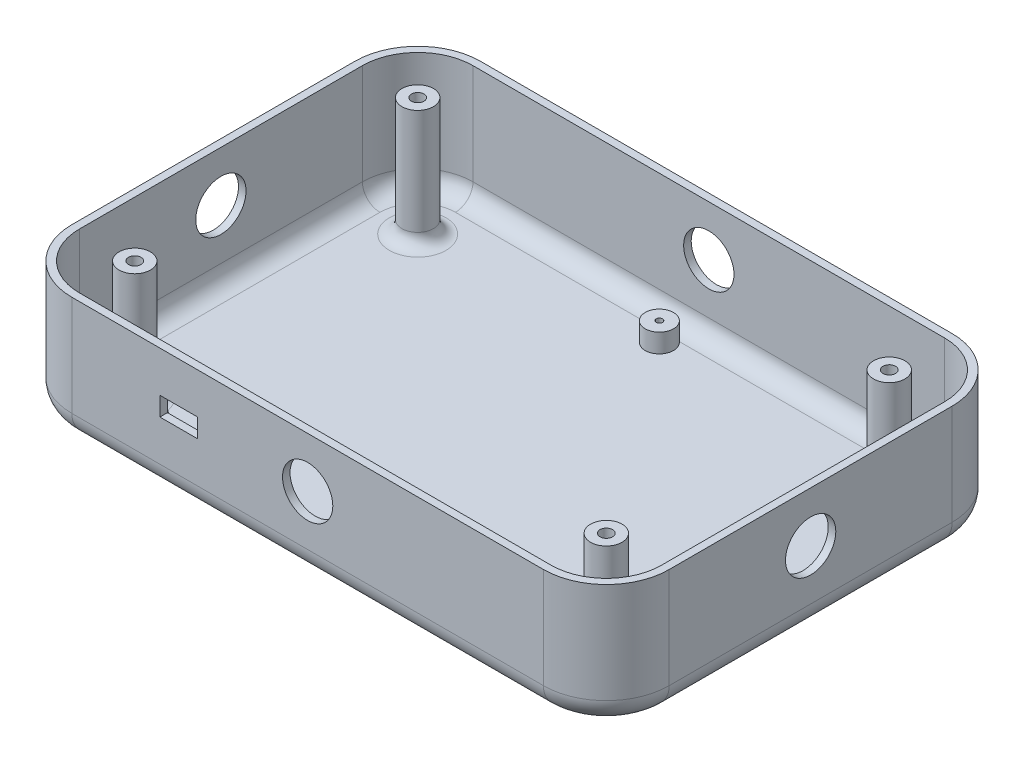
SolidWorks part; units mm, degrees
ref_plane "Front Plane" through (0, 0, 0) normal (0, 0, 1) x (1, 0, 0)
ref_plane "Top Plane" through (0, 0, 0) normal (0, 1, 0) x (1, 0, 0)
ref_plane "Right Plane" through (0, 0, 0) normal (1, 0, 0) x (0, 0, -1)
sketch "Sketch1" plane through (0, 0, 0) normal (0, 1, 0) x (1, 0, 0)
  line L1 (0, 0) -> (95, 0)
  line L2 (0, 0) -> (0, 65)
  line L3 (0, 65) -> (95, 65)
  line L4 (95, 0) -> (95, 65)
  dimension "D1" = 95
  dimension "D2" = 65
extrude "Boss-Extrude1" add sketch "Sketch1" along normal blind 20
fillet "Fillet1" radius 10 4 edges at (95, 10, 0) (95, 10, -65) (0, 10, -65) (0, 10, 0)
fillet "Fillet2" radius 4 8 edges at (92.0711, 0, -62.0711) (47.5, 0, -65) (2.9289, 0, -62.0711) (0, 0, -32.5) (2.9289, 0, -2.9289) (47.5, 0, 0) (92.0711, 0, -2.9289) (95, 0, -32.5)
shell "Shell1" thickness 1.2
sketch "Sketch4" plane through (0, 1.2, 0) normal (0, 1, 0) x (1, 0, 0)
  line L0 (85, 63.8) -> (10, 63.8) construction
  line L1 (1.2, 55) -> (1.2, 10) construction
  circle A0 centre (44.14, 59.3) radius 2.25
  circle A1 centre (16.2, 5.96) radius 2.25
  dimension "D1" = 4.5
  dimension "D3" = 53.34
  dimension "D2" = 27.94
  dimension "D4" = 4.5
  dimension "D5" = 15
extrude "Platinenzapfen" add sketch "Sketch4" along normal blind 3 contours A1 | A0
sketch "Sketch5" plane through (0, 1.2, 0) normal (0, 1, 0) x (1, 0, 0)
  circle A0 centre (10, 55) radius 2.5
  circle A1 centre (85, 55) radius 2.5
  circle A2 centre (85, 10) radius 2.5
  circle A3 centre (10, 10) radius 2.5
  arc A4 (91, 55) -> (85, 61) centre (85, 55) ccw construction
  arc A5 (85, 4) -> (91, 10) centre (85, 10) ccw construction
  arc A6 (4, 10) -> (10, 4) centre (10, 10) ccw construction
  arc A7 (10, 61) -> (4, 55) centre (10, 55) ccw construction
  dimension "D1" = 5
extrude "Boss-Extrude3" add sketch "Sketch5" along normal up to surface (18.8 mm away) up to face at (47.5, 20, -32.5)
sketch "Sketch7" plane through (0, 20, 0) normal (0, 1, 0) x (1, 0, 0)
  circle A0 centre (10, 55) radius 1
  circle A1 centre (85, 55) radius 1
  circle A2 centre (85, 10) radius 1
  circle A3 centre (10, 10) radius 1
  dimension "D1" = 2
extrude "Cut-Extrude2" cut sketch "Sketch7" against normal blind 10
fillet "Fillet3" radius 2 4 edges at (85, 1.2, -12.5) (10, 1.2, -12.5) (85, 1.2, -57.5) (10, 1.2, -57.5)
sketch "Sketch8" plane through (0, 4.2, 0) normal (0, 1, 0) x (1, 0, 0)
  circle A0 centre (44.14, 59.3) radius 0.5
  circle A1 centre (16.2, 5.96) radius 0.5
  dimension "D1" = 1
extrude "Cut-Extrude3" cut sketch "Sketch8" against normal blind 2
sketch "Sketch9" plane through (0, 0, -65) normal (0, 0, -1) x (-1, 0, 0)
  line L0 (-85, 20) -> (-10, 20) construction
  line L3 (-10, 4) -> (-10, 20) construction
  circle A0 centre (-47.5, 12) radius 4
  point P5 (-47.5, 20)
  point P14 (-10, 12)
  dimension "D1" = 8
extrude "Cut-Extrude4" cut sketch "Sketch9" against normal up to next
sketch "Sketch2" plane through (0, 0, 0) normal (0, 0, 1) x (1, 0, 0)
  line L0 (85, 4) -> (85, 20) construction
  line L1 (10, 20) -> (85, 20) construction
  circle A0 centre (47.5, 12) radius 4
  point P5 (85, 12)
  point P9 (47.5, 20)
  dimension "D1" = 8
extrude "Cut-Extrude1" cut sketch "Sketch2" against normal up to next
sketch "Sketch10" plane through (0, 0, 0) normal (-1, 0, 0) x (0, 0, 1)
  line L0 (-10, 4) -> (-10, 20) construction
  line L1 (-55, 20) -> (-10, 20) construction
  circle A0 centre (-32.5, 12) radius 4
  point P4 (-10, 12)
  point P7 (-32.5, 20)
  dimension "D1" = 8
extrude "Cut-Extrude5" cut sketch "Sketch10" against normal up to next
sketch "Sketch11" plane through (95, 0, 0) normal (1, 0, 0) x (0, 0, -1)
  line L0 (10, 20) -> (55, 20) construction
  line L1 (55, 4) -> (55, 20) construction
  circle A0 centre (32.5, 12) radius 4
  point P4 (32.5, 20)
  point P7 (55, 12)
  dimension "D1" = 8
extrude "Cut-Extrude6" cut sketch "Sketch11" against normal up to next
sketch "Sketch12" plane through (0, 0, 0) normal (0, 0, 1) x (1, 0, 0)
  line L0 (85, 4) -> (85, 20) construction
  line L1 (24, 10.5) -> (30, 10.5)
  line L2 (24, 10.5) -> (24, 13.5)
  line L3 (24, 13.5) -> (30, 13.5)
  line L4 (30, 10.5) -> (30, 13.5)
  line L6 (10, 20) -> (10, 4) construction
  point P4 (24, 12)
  point P7 (30, 12)
  point P8 (85, 12)
  dimension "D1" = 3
  dimension "D2" = 6
  dimension "D3" = 14
extrude "Cut-Extrude7" cut sketch "Sketch12" against normal up to next
equation "\"D3@Sketch4\"=21 * 2.54"
equation "\"D2@Sketch4\"=11*2.54"
